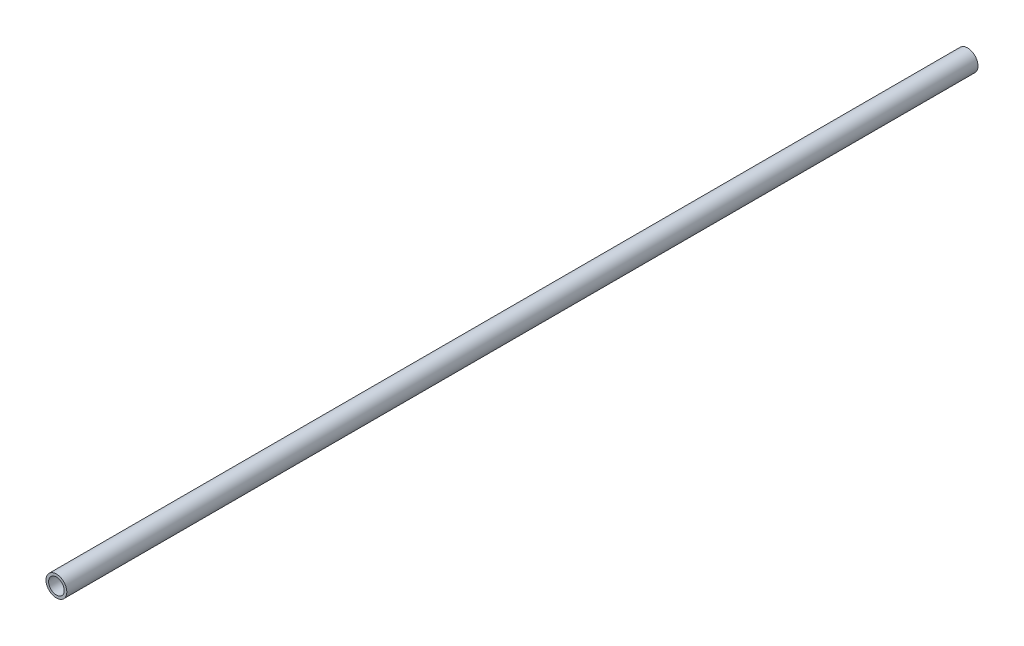
SolidWorks part; units mm, degrees
material "Alliage 1060"
ref_plane "Front" through (0, 0, 0) normal (0, 0, 1) x (1, 0, 0)
ref_plane "Top" through (0, 0, 0) normal (0, 1, 0) x (1, 0, 0)
ref_plane "Right" through (0, 0, 0) normal (1, 0, 0) x (0, 0, -1)
sketch "Esquisse1" plane through (0, 0, 0) normal (0, 0, 1) x (1, 0, 0)
  circle A0 centre (0, 0) radius 4
  dimension "D1" = 8
extrude "Extru.-Mince1" add sketch "Esquisse1" along normal blind 350 thin thin type one direction reverse wall 1
